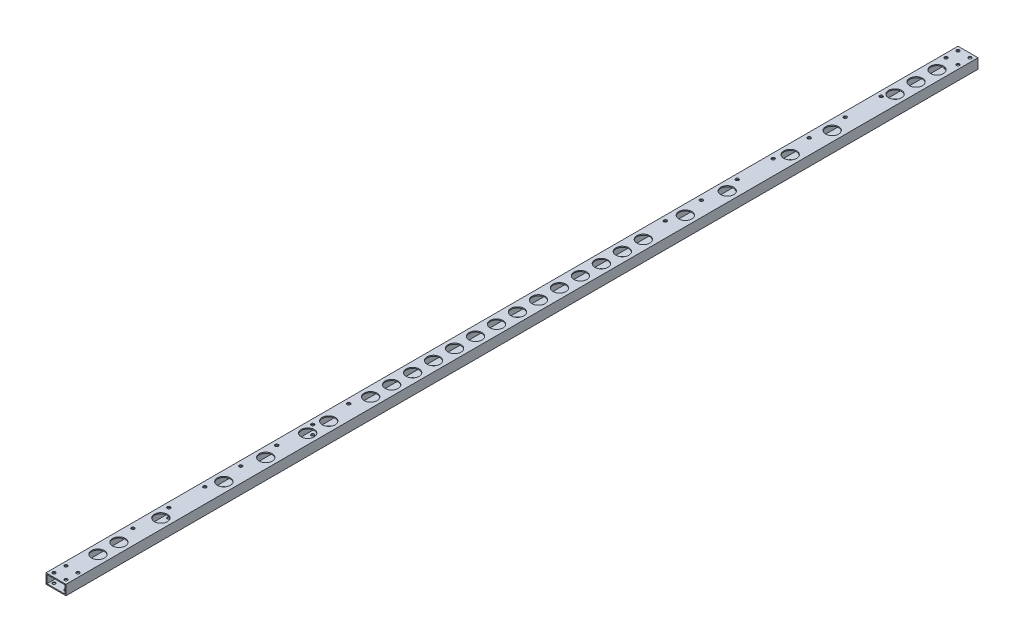
SolidWorks part; units mm, degrees
material "1100-H18 棒材(SS)"
ref_plane "前视基准面" through (0, 0, 0) normal (0, 0, 1) x (1, 0, 0)
ref_plane "上视基准面" through (0, 0, 0) normal (0, 1, 0) x (1, 0, 0)
ref_plane "右视基准面" through (0, 0, 0) normal (1, 0, 0) x (0, 0, -1)
other "Configuration Table"
sketch "草图1" plane through (0, 0, 0) normal (0, 0, 1) x (1, 0, 0)
  line L1 (0, 0) -> (20, 0)
  line L2 (0, 0) -> (0, 10)
  line L3 (0, 10) -> (20, 10)
  line L4 (20, 0) -> (20, 10)
  line L5 (1, 1) -> (19, 1)
  line L6 (1, 1) -> (1, 9)
  line L7 (1, 9) -> (19, 9)
  line L8 (19, 1) -> (19, 9)
  dimension "D1" = 20
  dimension "D2" = 10
  dimension "D3" = 1
  dimension "D4" = 1
  dimension "D5" = 1
  dimension "D6" = 1
extrude "凸台-拉伸1" add sketch "草图1" along normal blind 913
sketch "草图2" plane through (0, 0, 0) normal (0, -1, 0) x (1, 0, 0)
  circle A1 centre (5, 759) radius 1.6
  circle A2 centre (5, 759) radius 1.6
  circle A3 centre (5, 226) radius 1.6
  circle A5 centre (5, 795) radius 1.6
  circle A6 centre (5, 795) radius 1.6
  circle A7 centre (5, 226) radius 1.6
  circle A9 centre (5, 831) radius 1.6
  circle A10 centre (5, 831) radius 1.6
  circle A11 centre (5, 615) radius 1.6
  circle A12 centre (5, 615) radius 1.6
  circle A15 centre (5, 651) radius 1.6
  circle A16 centre (5, 651) radius 1.6
  circle A19 centre (5, 687) radius 1.6
  circle A20 centre (5, 687) radius 1.6
  circle A21 centre (5, 262) radius 1.6
  circle A23 centre (5, 723) radius 1.6
  circle A24 centre (5, 723) radius 1.6
  circle A25 centre (5, 262) radius 1.6
  circle A31 centre (5, 298) radius 1.6
  circle A32 centre (5, 298) radius 1.6
  circle A33 centre (5, 82) radius 1.6
  circle A34 centre (5, 82) radius 1.6
  circle A37 centre (5, 118) radius 1.6
  circle A38 centre (5, 118) radius 1.6
  circle A41 centre (5, 154) radius 1.6
  circle A42 centre (5, 154) radius 1.6
  circle A45 centre (5, 190) radius 1.6
  circle A46 centre (5, 190) radius 1.6
  dimension "D1" = 0
  dimension "D2" = 0
  dimension "D3" = 0
  dimension "D5" = 0
  dimension "D6" = 0
  dimension "D7" = 0
  dimension "D8" = 0
  dimension "D10" = 0
  dimension "D11" = 0
  dimension "D12" = 0
  dimension "D13" = 0
  dimension "D16" = 0
  dimension "D18" = 0
  dimension "D20" = 0
extrude "切除-拉伸1" cut sketch "草图2" against normal through all
sketch "草图3" plane through (0, 10, 0) normal (0, 1, 0) x (1, 0, 0)
  line L0 (20, -913) -> (20, 0) construction
  line L1 (20, 0) -> (0, 0) construction
  circle A0 centre (10, -10) radius 6.5 construction
  circle A1 centre (10, -31) radius 6.5
  circle A2 centre (10, -52) radius 6.5
  circle A3 centre (10, -73) radius 6.5
  circle A4 centre (10, -94) radius 6.5 [skipped]
  circle A5 centre (10, -115) radius 6.5 [skipped]
  circle A6 centre (10, -136) radius 6.5
  circle A7 centre (10, -157) radius 6.5 [skipped]
  circle A8 centre (10, -178) radius 6.5
  circle A9 centre (10, -199) radius 6.5 [skipped]
  circle A10 centre (10, -220) radius 6.5 [skipped]
  circle A11 centre (10, -241) radius 6.5
  circle A12 centre (10, -262) radius 6.5 [skipped]
  circle A13 centre (10, -283) radius 6.5
  circle A14 centre (10, -304) radius 6.5 [skipped]
  circle A15 centre (10, -325) radius 6.5
  circle A16 centre (10, -346) radius 6.5
  circle A17 centre (10, -367) radius 6.5
  circle A18 centre (10, -388) radius 6.5
  circle A19 centre (10, -409) radius 6.5
  circle A20 centre (10, -430) radius 6.5
  circle A21 centre (10, -451) radius 6.5
  circle A22 centre (10, -472) radius 6.5
  circle A23 centre (10, -493) radius 6.5
  circle A24 centre (10, -514) radius 6.5
  circle A25 centre (10, -535) radius 6.5
  circle A26 centre (10, -556) radius 6.5
  circle A27 centre (10, -577) radius 6.5
  circle A28 centre (10, -598) radius 6.5
  circle A29 centre (10, -619) radius 6.5 [skipped]
  circle A30 centre (10, -640) radius 6.5
  circle A31 centre (10, -661) radius 6.5
  circle A32 centre (10, -682) radius 6.5 [skipped]
  circle A33 centre (10, -703) radius 6.5
  circle A34 centre (10, -724) radius 6.5 [skipped]
  circle A35 centre (10, -745) radius 6.5
  circle A36 centre (10, -766) radius 6.5 [skipped]
  circle A37 centre (10, -787) radius 6.5 [skipped]
  circle A38 centre (10, -808) radius 6.5
  circle A39 centre (10, -829) radius 6.5 [skipped]
  circle A40 centre (10, -850) radius 6.5
  circle A41 centre (10, -871) radius 6.5
  circle A42 centre (10, -892) radius 6.5 construction
  dimension "D1" = 13
  dimension "D2" = 10
  dimension "D3" = 10
  dimension "D5" = 21
  dimension "D4" = 43
extrude "切除-拉伸2" cut sketch "草图3" against normal through all
sketch "草图4" plane through (0, 10, 0) normal (0, 1, 0) x (1, 0, 0)
  circle A1 centre (16, -909) radius 1.575
  circle A2 centre (16, -909) radius 1.575
  circle A3 centre (4, -909) radius 1.575
  circle A4 centre (4, -909) radius 1.575
  circle A5 centre (4, -897) radius 1.575
  circle A6 centre (4, -897) radius 1.575
  circle A7 centre (16, -897) radius 1.575
  circle A8 centre (16, -897) radius 1.575
  circle A9 centre (16, -929) radius 1.575
  circle A10 centre (16, -929) radius 1.575 construction
  circle A11 centre (16, -917) radius 1.575
  circle A12 centre (16, -917) radius 1.575 construction
  circle A13 centre (26, -929) radius 1.575
  circle A14 centre (26, -929) radius 1.575 construction
  circle A15 centre (26, -917) radius 1.575
  circle A16 centre (26, -917) radius 1.575 construction
  circle A17 centre (4, -917) radius 1.575
  circle A18 centre (4, -917) radius 1.575 construction
  circle A19 centre (4, -929) radius 1.575
  circle A20 centre (4, -929) radius 1.575 construction
  circle A21 centre (-6, -929) radius 1.575
  circle A22 centre (-6, -929) radius 1.575 construction
  circle A23 centre (-6, -917) radius 1.575
  circle A24 centre (-6, -917) radius 1.575 construction
  circle A25 centre (16, -4) radius 1.575
  circle A26 centre (16, -4) radius 1.575
  circle A27 centre (4, -4) radius 1.575
  circle A28 centre (4, -4) radius 1.575
  circle A29 centre (4, -16) radius 1.575
  circle A30 centre (4, -16) radius 1.575
  circle A31 centre (16, -16) radius 1.575
  circle A32 centre (16, -16) radius 1.575
  circle A33 centre (16, 16) radius 1.575
  circle A34 centre (16, 16) radius 1.575 construction
  circle A35 centre (16, 4) radius 1.575
  circle A36 centre (16, 4) radius 1.575 construction
  circle A37 centre (26, 16) radius 1.575
  circle A38 centre (26, 16) radius 1.575 construction
  circle A39 centre (26, 4) radius 1.575
  circle A40 centre (26, 4) radius 1.575 construction
  circle A41 centre (4, 4) radius 1.575
  circle A42 centre (4, 4) radius 1.575 construction
  circle A43 centre (4, 16) radius 1.575
  circle A44 centre (4, 16) radius 1.575 construction
  circle A45 centre (-6, 16) radius 1.575
  circle A46 centre (-6, 16) radius 1.575 construction
  circle A47 centre (-6, 4) radius 1.575
  circle A48 centre (-6, 4) radius 1.575 construction
  dimension "D1" = 0
  dimension "D2" = 0
  dimension "D3" = 0
  dimension "D4" = 0
  dimension "D5" = 0
  dimension "D6" = 0
  dimension "D7" = 0
  dimension "D8" = 0
  dimension "D9" = 0
  dimension "D10" = 0
  dimension "D11" = 0
  dimension "D12" = 0
  dimension "D13" = 0
  dimension "D14" = 0
  dimension "D15" = 0
  dimension "D16" = 0
  dimension "D17" = 0
  dimension "D18" = 0
  dimension "D19" = 0
  dimension "D20" = 0
  dimension "D21" = 0
  dimension "D22" = 0
  dimension "D23" = 0
  dimension "D24" = 0
extrude "切除-拉伸3" cut sketch "草图4" against normal through all
